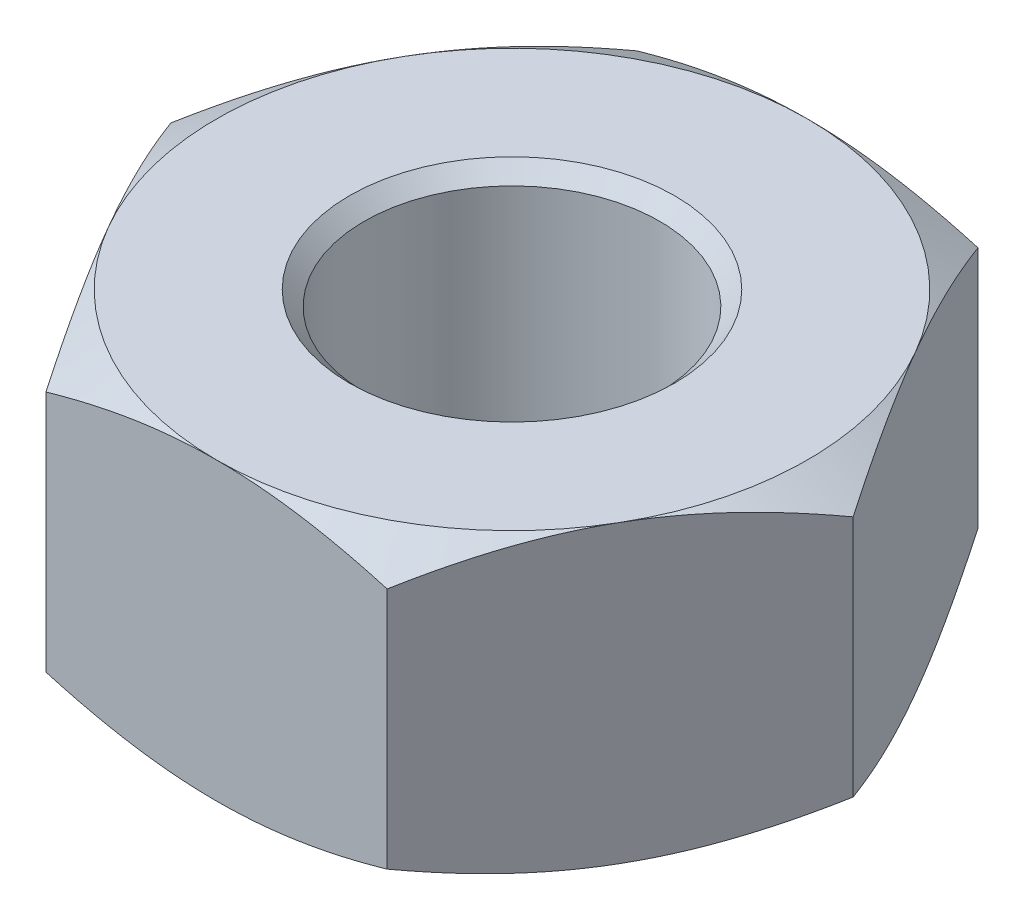
SolidWorks part; units mm, degrees
ref_plane "Front Plane" through (0, 0, 0) normal (0, 0, 1) x (1, 0, 0)
ref_plane "Top Plane" through (0, 0, 0) normal (0, 1, 0) x (1, 0, 0)
ref_plane "Right Plane" through (0, 0, 0) normal (1, 0, 0) x (0, 0, -1)
sketch "Sketch2" plane through (0, 0, 0) normal (0, 1, 0) x (1, 0, 0)
  line L1 (1.7321, 0) -> (0.866, 1.5)
  line L2 (0.866, 1.5) -> (-0.866, 1.5)
  line L3 (-0.866, 1.5) -> (-1.7321, 0)
  line L4 (-1.7321, 0) -> (-0.866, -1.5)
  line L5 (-0.866, -1.5) -> (0.866, -1.5)
  line L6 (0.866, -1.5) -> (1.7321, 0)
  circle A0 centre (0, 0) radius 0.75
  circle A1 centre (0, 0) radius 1.5 construction
  dimension "D1" = 1.5
  dimension "D2" = 3
extrude "Boss-Extrude1" add sketch "Sketch2" along normal blind 1.5
sketch "Sketch3" plane through (0, 0, 0) normal (0, 1, 0) x (1, 0, 0)
  circle A0 centre (0, 0) radius 1.5 construction
  circle A1 centre (0, 0) radius 1.5
extrude "Cut-Extrude1" cut sketch "Sketch3" along normal blind 3.25 draft 60 flip side to cut
sketch "Sketch4" plane through (0, 1.5, 0) normal (0, 1, 0) x (1, 0, 0)
  circle A1 centre (0, 0) radius 1.5
  circle A2 centre (0, 0) radius 1.5
  dimension "D1" = 0
extrude "Cut-Extrude2" cut sketch "Sketch4" against normal blind 3.25 draft 60 flip side to cut
chamfer "Chamfer1" distance 0.075 angle 45 2 edges at (0, 0, 0.75) (0, 1.5, 0.75)
